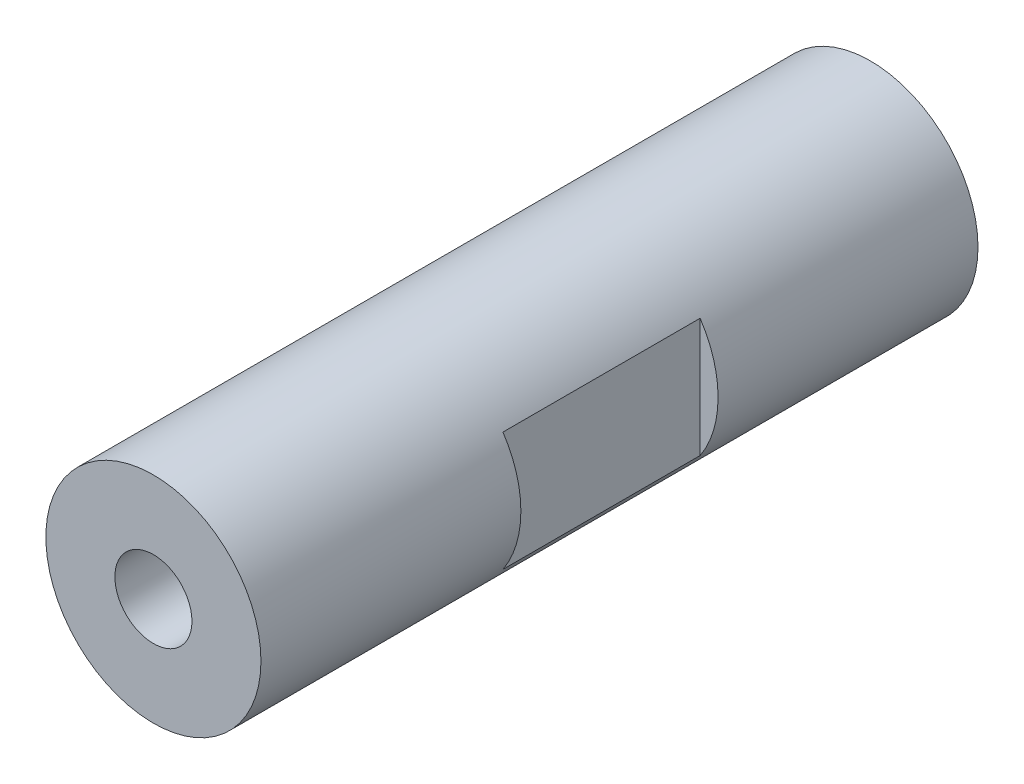
SolidWorks part; units mm, degrees
ref_plane "Спереди" through (0, 0, 0) normal (0, 0, 1) x (1, 0, 0)
ref_plane "Сверху" through (0, 0, 0) normal (0, 1, 0) x (1, 0, 0)
ref_plane "Справа" through (0, 0, 0) normal (1, 0, 0) x (0, 0, -1)
sketch "Эскиз1" plane through (0, 0, 0) normal (0, 0, 1) x (1, 0, 0)
  circle A0 centre (0, 0) radius 6
  circle A1 centre (0, 0) radius 2.15
  dimension "D1" = 12
  dimension "D2" = 4.3
extrude "Бобышка-Вытянуть1" add sketch "Эскиз1" along normal blind 40
sketch "Эскиз2" plane through (0, 0, 0) normal (0, 1, 0) x (1, 0, 0)
  line L0 (6, -40) -> (6, 0) construction
  line L1 (-6, -14.5) -> (-5, -14.5)
  line L2 (-6, -14.5) -> (-6, -25.5)
  line L3 (-6, -25.5) -> (-5, -25.5)
  line L4 (-5, -14.5) -> (-5, -25.5)
  line L5 (6, -14.5) -> (5, -14.5)
  line L6 (6, -14.5) -> (6, -25.5)
  line L7 (6, -25.5) -> (5, -25.5)
  line L8 (5, -14.5) -> (5, -25.5)
  line L9 (-6, 0) -> (-6, -40) construction
  line L10 (-6, -40) -> (6, -40) construction
  point P8 (6, -10.6202)
  point P11 (-6, -10.5259)
  point P14 (-6, -24.4758)
  point P15 (-6, -20)
  dimension "D1" = 11
  dimension "D2" = 20
  dimension "D3" = 10
extrude "Вырез-Вытянуть1" cut sketch "Эскиз2" against normal through all both and the other way through all
